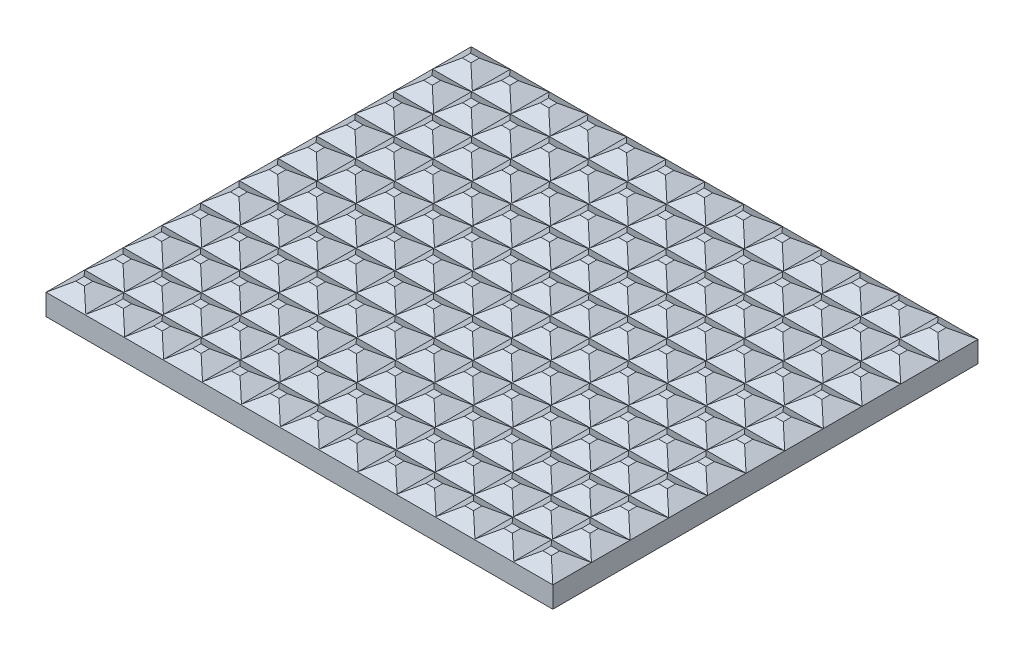
SolidWorks part; units mm, degrees
material "ABS"
ref_plane "Front Plane" through (0, 0, 0) normal (0, 0, 1) x (1, 0, 0)
ref_plane "Top Plane" through (0, 0, 0) normal (0, 1, 0) x (1, 0, 0)
ref_plane "Right Plane" through (0, 0, 0) normal (1, 0, 0) x (0, 0, -1)
sketch "Sketch1" plane through (0, 0, 0) normal (0, 1, 0) x (1, 0, 0)
  line L6 (-29.5, 24.75) -> (29.5, 24.75)
  line L28 (-29.5, 24.75) -> (-29.5, -24.75)
  line L29 (-29.5, -24.75) -> (29.5, -24.75)
  line L30 (29.5, 24.75) -> (29.5, -24.75)
  line L31 (-29.5, 24.75) -> (29.5, -24.75) construction
  line L32 (-29.5, -24.75) -> (29.5, 24.75) construction
  circle A1 centre (0, 0) radius 3
  point P0 (0, 0)
  dimension "D3" = 6
  dimension "D1" = 59
  dimension "D2" = 49.5
extrude "Boss-Extrude1" add sketch "Sketch1" along normal blind 1.5
sketch "Sketch2" plane through (0, 0, -24.75) normal (0, 0, -1) x (-1, 0, 0)
  line L0 (2.265, 2.5) -> (4.53, 4)
  line L1 (-29.5, 1.5) -> (29.5, 1.5)
  line L4 (29.5, 1.5) -> (29.5, 2.4636)
  line L6 (4.53, 4) -> (6.795, 2.5)
  line L56 (-2.265, 2.5) -> (0, 4)
  line L57 (0, 4) -> (2.265, 2.5)
  line L58 (-29.5, 1.5) -> (29.5, 1.5) construction
  line L59 (-29.5, 1.5) -> (-29.5, 2.4636)
  line L60 (6.795, 2.5) -> (9.06, 4)
  line L61 (9.06, 4) -> (11.325, 2.5)
  line L62 (11.325, 2.5) -> (13.59, 4)
  line L63 (13.59, 4) -> (15.855, 2.5)
  line L64 (15.855, 2.5) -> (18.12, 4)
  line L65 (18.12, 4) -> (20.385, 2.5)
  line L66 (20.385, 2.5) -> (22.65, 4)
  line L67 (22.65, 4) -> (24.915, 2.5)
  line L68 (24.915, 2.5) -> (27.18, 4)
  line L69 (27.18, 4) -> (29.445, 2.5)
  line L70 (29.445, 2.5) -> (29.5, 2.4636)
  line L71 (0, 0.825) -> (0, -0.825) construction
  line L72 (-29.445, 2.5) -> (-29.5, 2.4636)
  line L73 (-27.18, 4) -> (-29.445, 2.5)
  line L74 (-24.915, 2.5) -> (-27.18, 4)
  line L75 (-22.65, 4) -> (-24.915, 2.5)
  line L76 (-20.385, 2.5) -> (-22.65, 4)
  line L77 (-18.12, 4) -> (-20.385, 2.5)
  line L78 (-15.855, 2.5) -> (-18.12, 4)
  line L79 (-13.59, 4) -> (-15.855, 2.5)
  line L80 (-11.325, 2.5) -> (-13.59, 4)
  line L81 (-9.06, 4) -> (-11.325, 2.5)
  line L82 (-6.795, 2.5) -> (-9.06, 4)
  line L83 (-4.53, 4) -> (-6.795, 2.5)
  line L84 (-2.265, 2.5) -> (-4.53, 4)
  dimension "D1" = 7
  dimension "D2" = 1.5
  dimension "D3" = 4.53
extrude "Boss-Extrude2" add sketch "Sketch2" against normal up to surface (49.5 mm away) up to face at (0, 0.75, 24.75)
sketch "Sketch3" plane through (0, 0, 0) normal (0, -1, 0) x (-1, 0, 0)
  line L0 (0, 0.825) -> (0, -0.825) construction
  line L2 (-1.75, -2.4367) -> (-1.75, -5)
  line L3 (-1.75, -5) -> (1.75, -5)
  line L4 (1.75, -2.4367) -> (1.75, -5)
  arc A0 (1.75, -2.4367) -> (-1.75, -2.4367) centre (0, 0) ccw
  dimension "D2" = 6
  dimension "D1" = 3.5
  dimension "D3" = 5
  dimension "D4" = 1.75
extrude "Cut-Extrude1" cut sketch "Sketch3" against normal blind 2
sketch "Sketch5" plane through (0, 1.5, 0) normal (0, -1, 0) x (1, 0, 0)
  circle A0 centre (0, 0) radius 3
  dimension "D1" = 6
extrude "Boss-Extrude3" [suppressed] add sketch "Sketch5" along normal blind 0.5
sketch "Sketch6" plane through (0, 2, 0) normal (0, -1, 0) x (1, 0, 0)
  line L1 (1.75, 5) -> (-1.75, 5)
  line L2 (1.75, 5) -> (1.75, 2.4367)
  line L3 (1.75, 2.4367) -> (-1.75, 2.4367)
  line L4 (-1.75, 5) -> (-1.75, 2.4367)
extrude "Cut-Extrude4" [suppressed] cut sketch "Sketch6" against normal blind 0.5
chamfer "Chamfer3" distance 1.5 angle 45 1 edges at (0, 0, 5)
sketch "Sketch9" plane through (29.5, 0, 0) normal (1, 0, 0) x (0, 0, -1)
  line L53 (-24.75, 2.4636) -> (-22.65, 4)
  line L55 (-22.65, 4) -> (-20.25, 2.4636)
  line L57 (-20.25, 2.4636) -> (-18.15, 4)
  line L58 (-18.15, 4) -> (-15.75, 2.4636)
  line L59 (-15.75, 2.4636) -> (-13.65, 4)
  line L60 (-13.65, 4) -> (-11.25, 2.4636)
  line L61 (-11.25, 2.4636) -> (-9.15, 4)
  line L62 (-9.15, 4) -> (-6.75, 2.4636)
  line L63 (-6.75, 2.4636) -> (-4.65, 4)
  line L64 (-4.65, 4) -> (-2.25, 2.4636)
  line L65 (-2.25, 2.4636) -> (-0.15, 4)
  line L66 (-0.15, 4) -> (2.25, 2.4636)
  line L67 (2.25, 2.4636) -> (4.35, 4)
  line L68 (4.35, 4) -> (6.75, 2.4636)
  line L69 (6.75, 2.4636) -> (8.85, 4)
  line L70 (8.85, 4) -> (11.25, 2.4636)
  line L71 (11.25, 2.4636) -> (13.35, 4)
  line L72 (13.35, 4) -> (15.75, 2.4636)
  line L73 (15.75, 2.4636) -> (17.85, 4)
  line L74 (17.85, 4) -> (20.25, 2.4636)
  line L75 (20.25, 2.4636) -> (22.35, 4)
  line L76 (22.35, 4) -> (24.75, 2.4636)
  line L97 (-24.75, 2.4636) -> (-24.75, 6.4088)
  line L98 (-24.75, 6.4088) -> (24.75, 6.4088)
  line L100 (-24.75, 4) -> (24.75, 4) construction
  line L102 (-24.75, 2.4636) -> (-24.75, 4) construction
  line L103 (24.75, 2.4636) -> (24.75, 6.4088)
  line L105 (24.75, 2.4636) -> (26.85, 4) [skipped]
  line L106 (26.85, 4) -> (29.25, 2.4636) [skipped]
  line L107 (29.25, 2.4636) -> (31.35, 4) [skipped]
  line L108 (31.35, 4) -> (33.75, 2.4636) [skipped]
  line L109 (33.75, 2.4636) -> (35.85, 4) [skipped]
  line L110 (35.85, 4) -> (38.25, 2.4636) [skipped]
  line L111 (38.25, 2.4636) -> (40.35, 4) [skipped]
  line L112 (40.35, 4) -> (42.75, 2.4636) [skipped]
  line L113 (42.75, 2.4636) -> (44.85, 4) [skipped]
  line L114 (44.85, 4) -> (47.25, 2.4636) [skipped]
  line L115 (47.25, 2.4636) -> (49.35, 4) [skipped]
  line L116 (49.35, 4) -> (51.75, 2.4636) [skipped]
  line L117 (51.75, 2.4636) -> (53.85, 4) [skipped]
  line L118 (53.85, 4) -> (56.25, 2.4636) [skipped]
  line L119 (56.25, 2.4636) -> (58.35, 4) [skipped]
  line L120 (58.35, 4) -> (60.75, 2.4636) [skipped]
  line L121 (60.75, 2.4636) -> (62.85, 4) [skipped]
  line L122 (62.85, 4) -> (65.25, 2.4636) [skipped]
  line L123 (65.25, 2.4636) -> (67.35, 4) [skipped]
  line L124 (67.35, 4) -> (69.75, 2.4636) [skipped]
  dimension "D3" = 4.5
  dimension "D4" = 2.1
  dimension "D5" = 21
extrude "Cut-Extrude6" cut sketch "Sketch9" against normal through all
sketch "Sketch10" plane through (0, 0, 0) normal (0, 0, 1) x (1, 0, 0)
  line L0 (27.18, 4) -> (29.5, 2.4636) construction
  line L1 (31.1569, 5.8692) -> (-31.5744, 5.8692)
  line L2 (31.1569, 5.8692) -> (31.1569, 3.6689)
  line L3 (31.1569, 3.6689) -> (-31.5744, 3.6689)
  line L4 (-31.5744, 5.8692) -> (-31.5744, 3.6689)
  line L5 (24.915, 2.5) -> (27.18, 4) construction
  point P4 (27.68, 3.6689)
  point P8 (26.68, 3.6689)
  dimension "D1" = 1
extrude "Cut-Extrude7" cut sketch "Sketch10" against normal through all both and the other way through all
